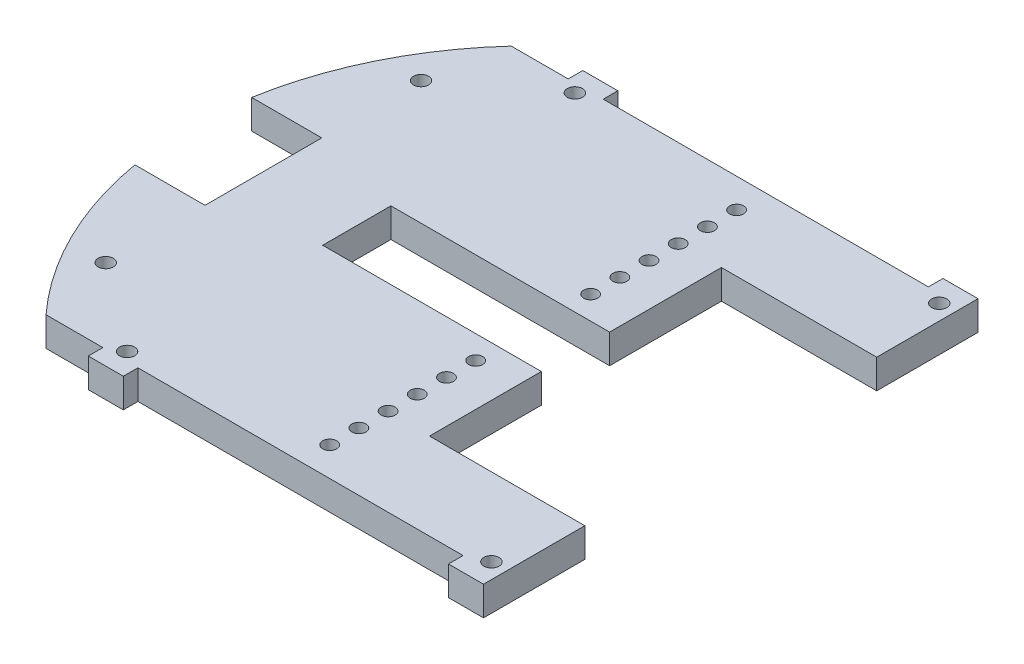
SolidWorks part; units mm, degrees
material "Acrylic (Medium-high impact)"
ref_plane "Front Plane" through (0, 0, 0) normal (0, 0, 1) x (1, 0, 0)
ref_plane "Top Plane" through (0, 0, 0) normal (0, 1, 0) x (1, 0, 0)
ref_plane "Right Plane" through (0, 0, 0) normal (1, 0, 0) x (0, 0, -1)
sketch "Sketch1" plane through (0, 0, 0) normal (0, 1, 0) x (1, 0, 0)
  line L0 (33.7767, 18.1873) -> (4.6272, 18.1873)
  line L1 (-30.9328, 38.3108) -> (-15.6928, 38.3108)
  line L2 (-15.6928, 38.3108) -> (-15.6928, 12.9108)
  line L3 (7.62, -24.9927) -> (78.3483, -24.9927)
  line L4 (33.7767, 18.1873) -> (52.1917, 18.1873)
  line L5 (52.1917, 18.1873) -> (52.1917, -6.1392)
  line L6 (52.1917, -6.1392) -> (85.9683, -6.1392)
  line L7 (85.9683, -6.1392) -> (85.9683, -24.9927)
  line L8 (42.9842, 0.9728) -> (42.9842, 18.1873) construction
  line L9 (82.6111, -23.0877) -> (82.6111, -6.1392) construction
  line L10 (82.6111, -23.0877) -> (85.9683, -23.0877) construction
  line L11 (3.3572, -23.0877) -> (3.3572, -6.1392) construction
  line L12 (3.3572, -23.0877) -> (0, -23.0877) construction
  line L13 (0, 76.2143) -> (0, 79.3893)
  line L14 (7.62, 76.2143) -> (7.62, 79.3893)
  line L15 (-30.9328, 25.6108) -> (90.9164, 25.6108) construction
  line L16 (-30.9328, 38.3108) -> (-30.9328, 12.9108) construction
  line L17 (90.9164, 24.0233) -> (90.9164, 27.1983) construction
  line L18 (3.3572, 74.3093) -> (0, 74.3093) construction
  line L19 (3.3572, 74.3093) -> (3.3572, 57.3608) construction
  line L20 (82.6111, 74.3093) -> (85.9683, 74.3093) construction
  line L21 (82.6111, 74.3093) -> (82.6111, 57.3608) construction
  line L22 (42.9842, 50.2488) -> (42.9842, 33.0343) construction
  line L23 (85.9683, 57.3608) -> (85.9683, 76.2143)
  line L24 (52.1917, 57.3608) -> (85.9683, 57.3608)
  line L25 (52.1917, 33.0343) -> (52.1917, 57.3608)
  line L26 (33.7767, 33.0343) -> (52.1917, 33.0343)
  line L27 (7.62, 76.2143) -> (78.3483, 76.2143)
  line L28 (-15.6928, 12.9108) -> (-30.9328, 12.9108)
  line L30 (33.7767, 33.0343) -> (4.6272, 33.0343)
  line L31 (78.3483, 76.2143) -> (78.3483, 79.3893)
  line L32 (0, 76.2143) -> (-12.3719, 76.2143)
  line L33 (4.6272, 33.0343) -> (4.6272, 18.1873)
  line L34 (0, -24.9927) -> (-12.3719, -24.9927)
  line L35 (78.3483, 79.3893) -> (85.9683, 79.3893)
  line L36 (85.9683, 76.2143) -> (85.9683, 79.3893)
  line L37 (7.62, 79.3893) -> (0, 79.3893)
  line L38 (78.3483, -24.9927) -> (78.3483, -28.1677)
  line L39 (85.9683, -24.9927) -> (85.9683, -28.1677)
  line L40 (78.3483, -28.1677) -> (85.9683, -28.1677)
  line L41 (7.62, -24.9927) -> (7.62, -28.1677)
  line L42 (0, -24.9927) -> (0, -28.1677)
  line L43 (7.62, -28.1677) -> (0, -28.1677)
  circle A0 centre (3.3572, -23.0877) radius 1.651
  circle A1 centre (82.6111, -23.0877) radius 1.651
  circle A2 centre (42.9842, -12.2927) radius 1.524
  circle A3 centre (42.9842, -18.6427) radius 1.524
  circle A4 centre (42.9842, -5.9427) radius 1.524
  circle A5 centre (42.9842, 0.4073) radius 1.524
  circle A6 centre (42.9842, 6.7573) radius 1.524
  circle A7 centre (42.9842, 13.1073) radius 1.524
  circle A8 centre (42.9842, 38.1143) radius 1.524
  circle A9 centre (82.6111, 74.3093) radius 1.651
  circle A10 centre (3.3572, 74.3093) radius 1.651
  arc A11 (-30.9328, 12.9108) -> (110.2551, -7.5497) centre (42.9842, 25.6108) ccw construction
  arc A12 (-12.3719, 76.2143) -> (-30.9328, 38.3108) centre (42.9842, 25.6108) ccw
  arc A13 (110.2551, 58.7714) -> (-30.9328, 38.3108) centre (42.9842, 25.6108) ccw construction
  arc A14 (-12.3719, -24.9927) -> (-30.9328, 12.9108) centre (42.9842, 25.6108) cw
  circle A15 centre (-15.6928, 59.9008) radius 1.651
  circle A16 centre (-15.6928, -8.6792) radius 1.651
  circle A17 centre (-15.6928, 59.9008) radius 1.651 construction
  circle A18 centre (42.9842, 44.4643) radius 1.524
  circle A19 centre (42.9842, 50.8143) radius 1.524
  circle A20 centre (42.9842, 57.1643) radius 1.524
  circle A21 centre (42.9842, 63.5143) radius 1.524
  circle A22 centre (42.9842, 69.8643) radius 1.524
  dimension "D8" = 3.048
  dimension "D1" = 33.7767
  dimension "D2" = 63.5
  dimension "D3" = 6.35
  dimension "D4" = 20.32
  dimension "D5" = 116.9011
  dimension "D6" = 3.175
  dimension "D7" = 7.62
  dimension "D9" = 43.18
  dimension "D10" = 6
extrude "Boss-Extrude1" add sketch "Sketch1" along normal blind 6.35
